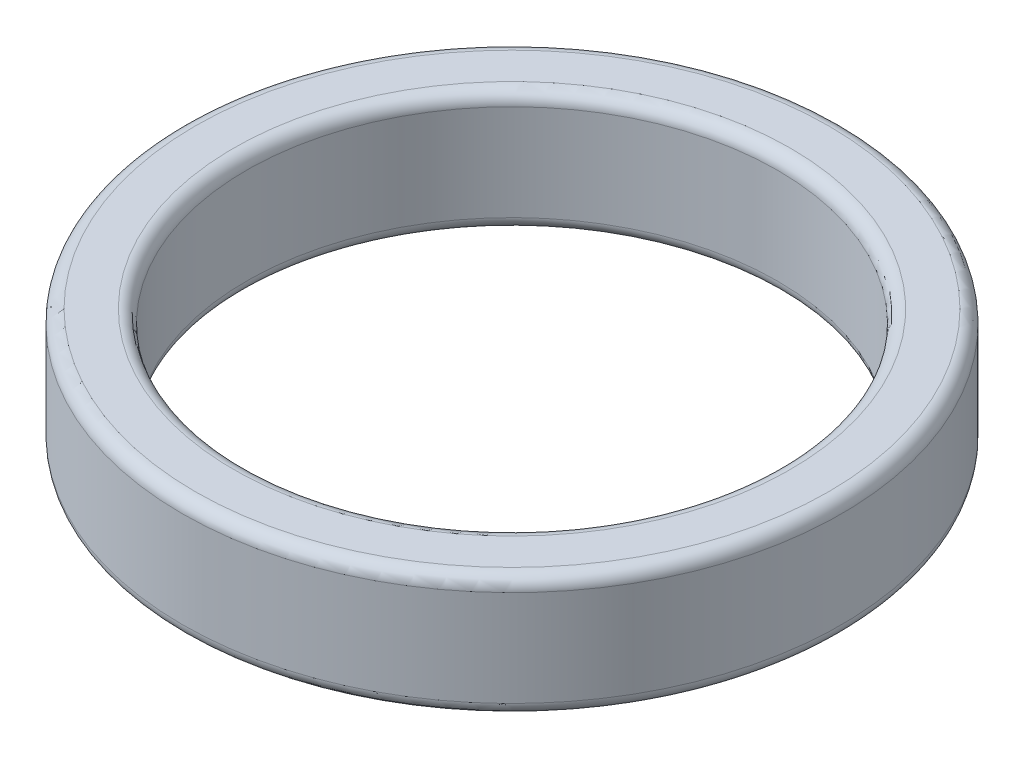
SolidWorks part; units mm, degrees
ref_plane "Спереди" through (0, 0, 0) normal (0, 0, 1) x (1, 0, 0)
ref_plane "Сверху" through (0, 0, 0) normal (0, 1, 0) x (1, 0, 0)
ref_plane "Справа" through (0, 0, 0) normal (1, 0, 0) x (0, 0, -1)
sketch "Эскиз1" plane through (0, 0, 0) normal (0, 0, 1) x (1, 0, 0)
  line L0 (0, 0) -> (0, 8.6241) construction
  line L1 (-4.35, 0.3) -> (-4.95, 0.3)
  line L2 (-4.15, 0.5) -> (-4.15, 2)
  line L4 (-5.15, 0.5) -> (-5.15, 2)
  line L5 (-4.95, 2.2) -> (-4.35, 2.2)
  arc A0 (-4.95, 0.3) -> (-5.15, 0.5) centre (-4.95, 0.5) cw
  arc A1 (-4.15, 0.5) -> (-4.35, 0.3) centre (-4.35, 0.5) cw
  arc A3 (-5.15, 2) -> (-4.95, 2.2) centre (-4.95, 2) cw
  arc A4 (-4.15, 2) -> (-4.35, 2.2) centre (-4.35, 2) ccw
  point P9 (-4.1, 0)
  point P12 (-3.1, 0)
  point P15 (-3.1, 1.8)
  dimension "D4" = 0.2
  dimension "D5" = 0.2
  dimension "D1" = 5.15
  dimension "D2" = 1
  dimension "D3" = 1.9
revolve "Повернуть1" add sketch "Эскиз1" angle 360 about L0
